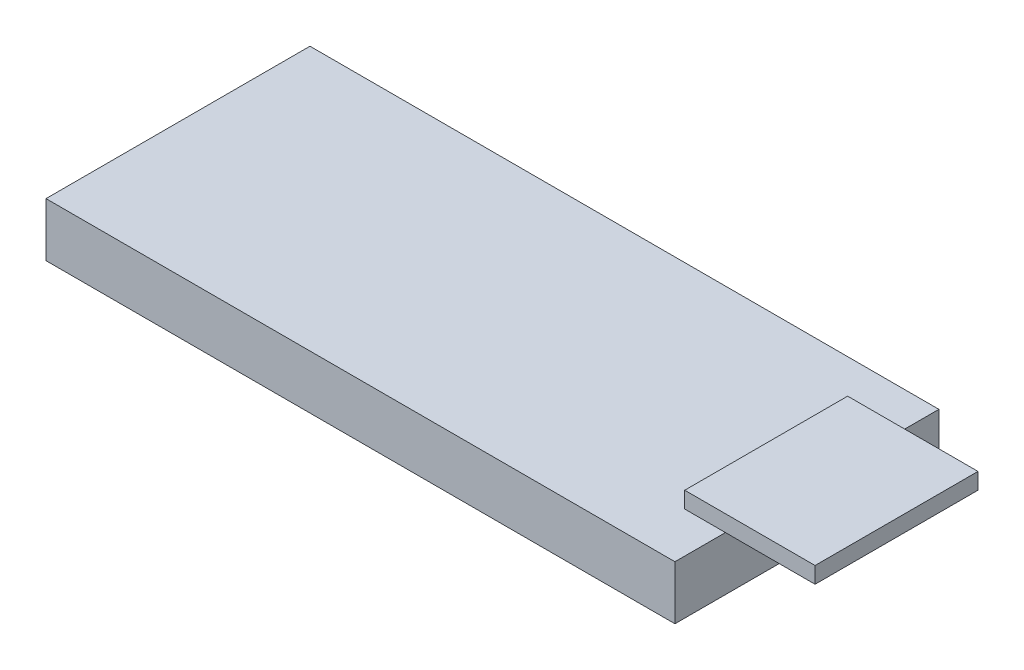
SolidWorks part; units mm, degrees
ref_plane "前视基准面" through (0, 0, 0) normal (0, 0, 1) x (1, 0, 0)
ref_plane "上视基准面" through (0, 0, 0) normal (0, 1, 0) x (1, 0, 0)
ref_plane "右视基准面" through (0, 0, 0) normal (1, 0, 0) x (0, 0, -1)
sketch "草图1" plane through (0, 0, 0) normal (0, 1, 0) x (1, 0, 0)
  line L1 (0, 0) -> (38.6, 0)
  line L2 (0, 0) -> (0, 16.2)
  line L3 (0, 16.2) -> (38.6, 16.2)
  line L4 (38.6, 0) -> (38.6, 16.2)
  dimension "D1" = 38.6
  dimension "D2" = 16.2
extrude "凸台-拉伸1" add sketch "草图1" along normal blind 3.3
sketch "草图2" plane through (0, 3.3, 0) normal (0, 1, 0) x (1, 0, 0)
  line L0 (38.6, 8.1) -> (24.7436, 8.1) construction
  line L1 (38.6, 0) -> (38.6, 16.2) construction
  line L3 (36.1, 3.1) -> (38.6, 3.1)
  line L4 (36.1, 3.1) -> (36.1, 13.1)
  line L5 (36.1, 13.1) -> (38.6, 13.1)
  line L6 (38.6, 3.1) -> (38.6, 13.1)
  line L7 (36.1, 3.1) -> (38.6, 13.1) construction
  line L8 (36.1, 13.1) -> (38.6, 3.1) construction
  point P4 (37.35, 8.1)
  dimension "D1" = 10
  dimension "D2" = 2.5
extrude "凸台-拉伸2" add sketch "草图2" along normal blind 1
sketch "草图3" plane through (38.6, 0, 0) normal (1, 0, 0) x (0, 0, -1)
  line L1 (3.1, 4.3) -> (13.1, 4.3)
  line L2 (3.1, 4.3) -> (3.1, 3.3)
  line L3 (3.1, 3.3) -> (13.1, 3.3)
  line L4 (13.1, 4.3) -> (13.1, 3.3)
extrude "凸台-拉伸3" add sketch "草图3" along normal blind 5.5
